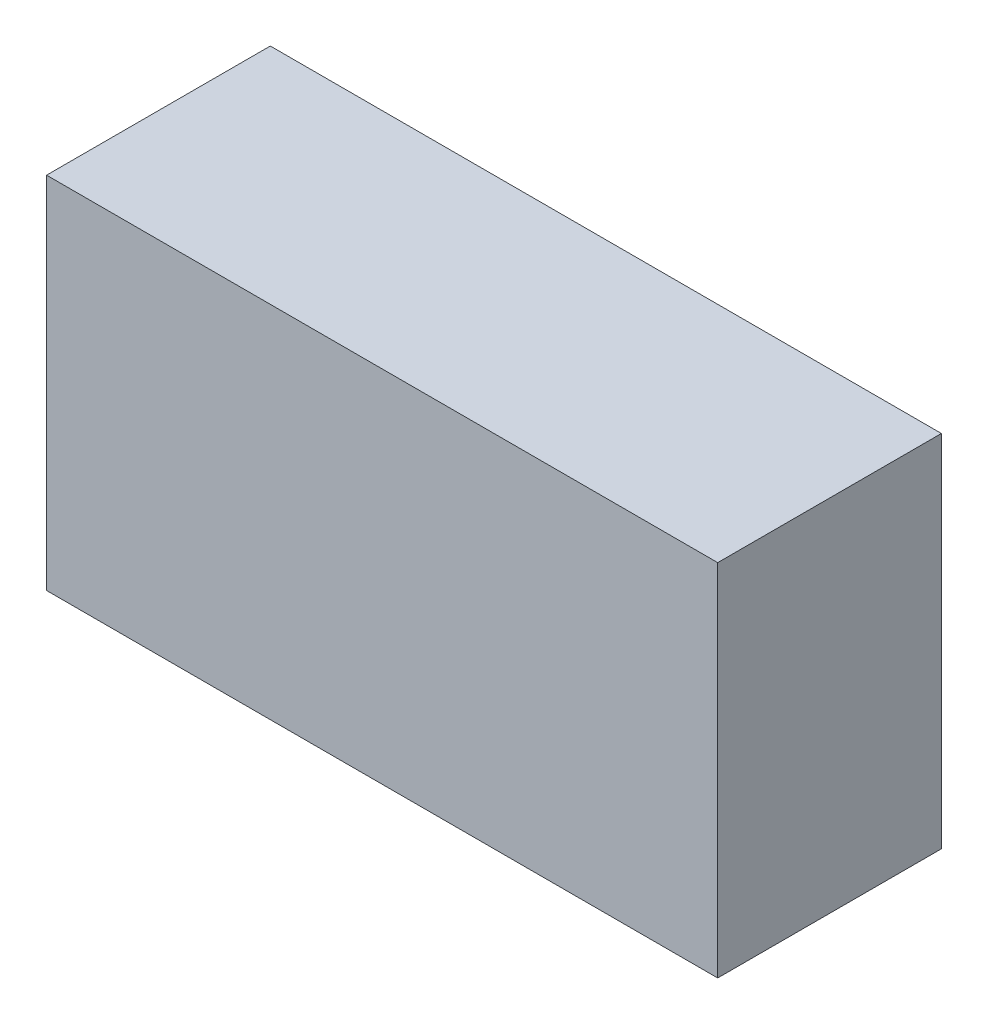
SolidWorks part; units mm, degrees
ref_plane "Front Plane" through (0, 0, 0) normal (0, 0, 1) x (1, 0, 0)
ref_plane "Top Plane" through (0, 0, 0) normal (0, 1, 0) x (1, 0, 0)
ref_plane "Right Plane" through (0, 0, 0) normal (1, 0, 0) x (0, 0, -1)
sketch "Sketch1" plane through (0, 0, 0) normal (1, 0, 0) x (0, 0, -1)
  line L1 (0, 0) -> (-50, 0)
  line L2 (0, 0) -> (0, -80.4)
  line L3 (0, -80.4) -> (-50, -80.4)
  line L4 (-50, 0) -> (-50, -80.4)
  dimension "D1" = 80.4
  dimension "D2" = 50
extrude "Boss-Extrude1" add sketch "Sketch1" along normal mid plane 150
